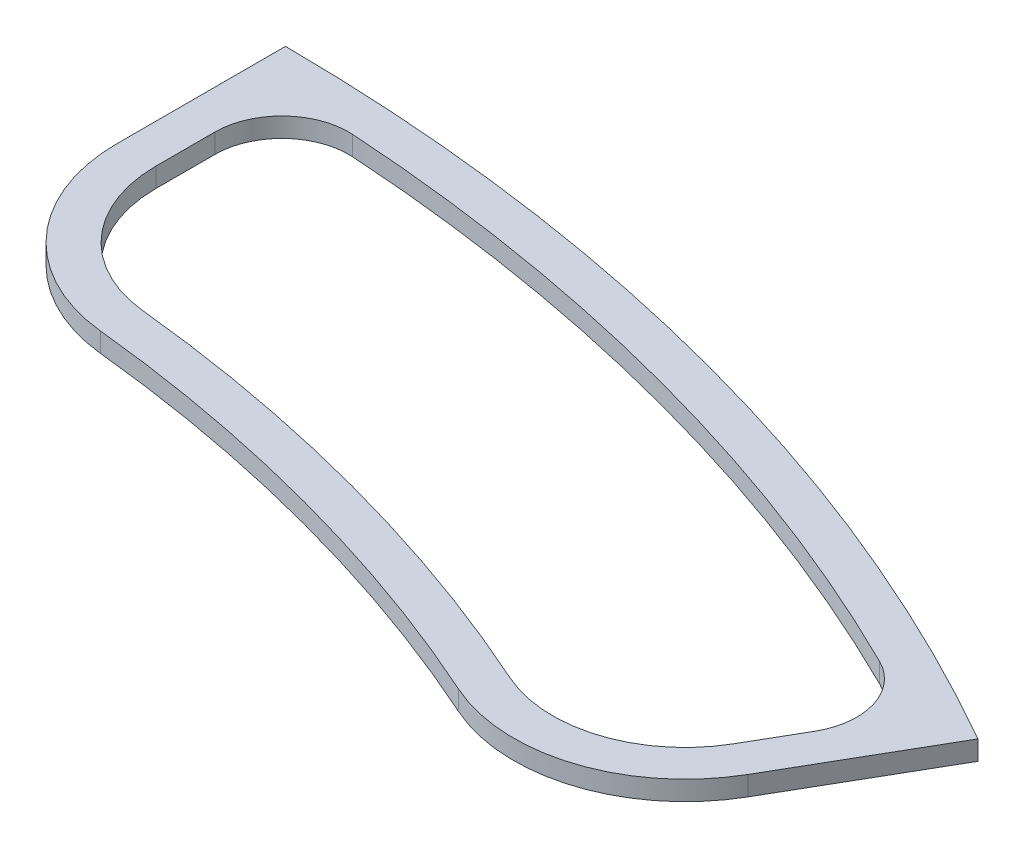
SolidWorks part; units mm, degrees
ref_plane "Front Plane" through (0, 0, 0) normal (0, 0, 1) x (1, 0, 0)
ref_plane "Top Plane" through (0, 0, 0) normal (0, 1, 0) x (1, 0, 0)
ref_plane "Right Plane" through (0, 0, 0) normal (1, 0, 0) x (0, 0, -1)
sketch "Sketch1" plane through (0, 0, 0) normal (0, 1, 0) x (1, 0, 0)
  line L0 (0, 0) -> (0, 297.5) construction
  line L1 (0, 0) -> (148.75, 257.6426) construction
  line L2 (204.8954, 357.8892) -> (-50.4142, -84.3199) construction
  line L3 (1.5, 359.3331) -> (1.5, -61.2496) construction
  line L4 (1.5, 297.4962) -> (1.5, 271.4962)
  line L5 (147.4491, 258.3893) -> (134.4491, 235.8726)
  circle A0 centre (0, 0) radius 297.5 construction
  arc A1 (1.5, 297.4962) -> (147.4491, 258.3893) centre (0, 0) cw
  arc A3 (1.5, 271.4962) -> (134.4491, 235.8726) centre (0, 0) cw
  dimension "D1" = 595
  dimension "D5" = 26
  dimension "D2" = 30
  dimension "D3" = 1.5
  dimension "D4" = 1.5
extrude "Boss-Extrude1" add sketch "Sketch1" along normal blind 3
sketch "Sketch3" plane through (0, 3, 0) normal (0, 1, 0) x (1, 0, 0)
  line L0 (7.5, 271.3968) -> (129.2032, 238.7865)
  line L3 (7.5, 297.4962) -> (7.5, 271.4962)
  line L4 (7.5, 286.4022) -> (7.5, 271.3968)
  line L8 (129.2529, 238.8726) -> (142.2529, 261.3893)
  line L9 (129.2032, 238.7865) -> (136.7059, 251.7816)
  arc A0 (134.4491, 235.8726) -> (1.5, 271.4962) centre (0, 0) ccw construction
  arc A1 (134.4491, 235.8726) -> (1.5, 271.4962) centre (0, 0) ccw construction
  arc A3 (141.8772, 248.9042) -> (1.5829, 286.496) centre (0, 0) ccw
  arc A4 (136.7059, 251.7816) -> (7.5, 286.4022) centre (0, 0) ccw
  dimension "D1" = 15
  dimension "D2" = 6
  dimension "D3" = 6
extrude "Cut-Extrude1" cut sketch "Sketch3" against normal blind 3
fillet "Fillet1" radius 10 2 edges at (7.5, 1.5, -286.4022) (136.7059, 1.5, -251.7816)
fillet "Fillet2" radius 3 2 edges at (129.2032, 1.5, -238.7865) (7.5, 1.5, -271.3968)
sketch "Sketch4" plane through (0, 3, 0) normal (0, 1, 0) x (1, 0, 0)
  line L0 (134.4491, 235.8726) -> (147.4491, 258.3893) construction
  line L1 (1.5, 297.4962) -> (1.5, 271.4962) construction
  line L2 (129.2529, 238.8726) -> (130.7365, 241.4423)
  line L3 (130.7365, 241.4423) -> (134.4491, 235.8726)
  line L4 (7.5, 271.4962) -> (7.5, 274.4635)
  line L5 (7.5, 274.4635) -> (1.5, 271.4962)
  arc A0 (134.4491, 235.8726) -> (100.7584, 224.967) centre (111.5613, 249.0869) cw
  arc A1 (100.7584, 224.967) -> (25.2242, 245.2064) centre (0, 0) ccw
  arc A2 (25.2242, 245.2064) -> (1.5, 271.4962) centre (27.9286, 271.4962) cw
  arc A3 (147.4491, 258.3893) -> (1.5, 297.4962) centre (0, 0) ccw construction
  arc A4 (127.2594, 256.6856) -> (18.1329, 285.926) centre (0, 0) ccw construction
  arc A5 (129.2529, 238.8726) -> (103.211, 230.4429) centre (111.5613, 249.0869) cw
  arc A6 (103.211, 230.4429) -> (25.8381, 251.1749) centre (0, 0) ccw
  arc A7 (25.8381, 251.1749) -> (7.5, 271.4962) centre (27.9286, 271.4962) cw
  dimension "D1" = 40
  dimension "D2" = 6
extrude "Boss-Extrude2" add sketch "Sketch4" against normal blind 3
sketch "Sketch5" plane through (0, 3, 0) normal (0, 1, 0) x (1, 0, 0)
  line L0 (131.4778, 242.7263) -> (133.8243, 246.7905)
  line L1 (7.5, 275.946) -> (7.5, 280.639)
  line L2 (7.5, 275.946) -> (7.5, 271.4962) construction
  line L3 (129.2529, 238.8726) -> (131.4778, 242.7263) construction
  line L4 (7.5, 275.946) -> (131.4778, 242.7263)
  arc A2 (18.4494, 290.9159) -> (7.5, 280.639) centre (17.7976, 280.639) ccw
  arc A3 (129.4803, 261.1653) -> (18.4494, 290.9159) centre (0, 0) ccw
  arc A4 (129.4803, 261.1653) -> (18.4494, 290.9159) centre (0, 0) ccw
  arc A5 (129.4803, 261.1653) -> (133.8243, 246.7905) centre (124.9063, 251.9393) cw
  arc A6 (18.1329, 285.926) -> (7.5, 275.946) centre (17.5, 275.946) ccw construction
  dimension "D1" = 5
extrude "Cut-Extrude2" cut sketch "Sketch5" against normal blind 3
